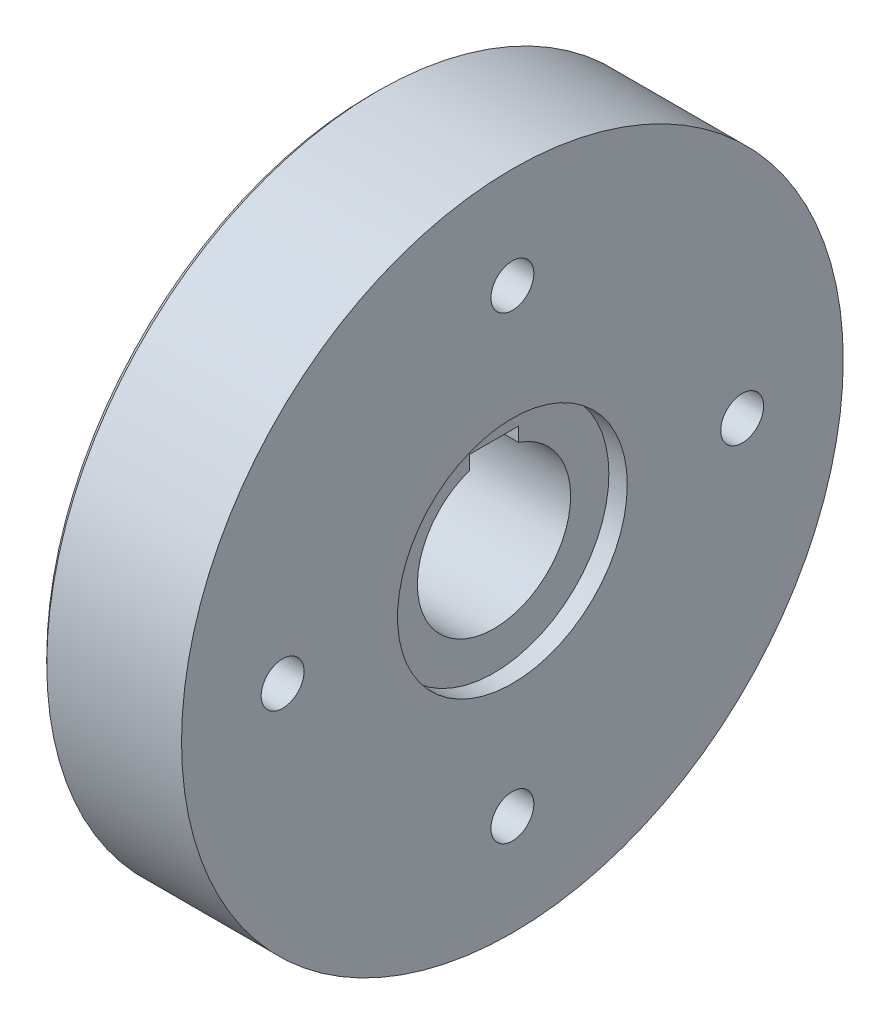
SolidWorks part; units mm, degrees
ref_plane "Front Plane" through (0, 0, 0) normal (0, 0, 1) x (1, 0, 0)
ref_plane "Top Plane" through (0, 0, 0) normal (0, 1, 0) x (1, 0, 0)
ref_plane "Right Plane" through (0, 0, 0) normal (1, 0, 0) x (0, 0, -1)
sketch "Sketch1" plane through (0, 0, 0) normal (0, 0, 1) x (1, 0, 0)
  line L0 (0, 0) -> (0, 15070.8085) construction
  line L1 (0, 0) -> (15070.8085, 0) construction
  line L2 (-40, 0) -> (40, 0)
  line L3 (-40, 25) -> (40, 25)
  line L4 (40, 108) -> (15, 108)
  line L5 (-40, 50) -> (15, 50)
  line L6 (15, 108) -> (15, 50)
  line L7 (-40, 50) -> (-40, 25)
  line L8 (40, 108) -> (40, 37.5)
  line L9 (40, 37.5) -> (45, 37.5)
  line L10 (45, 37.5) -> (45, 25)
  line L11 (45, 25) -> (40, 25)
  point P7 (0, 0)
  point P10 (0, 25)
  dimension "D1" = 80
  dimension "D2" = 50
  dimension "D3" = 216
  dimension "D4" = 25
  dimension "D5" = 100
  dimension "D6" = 75
  dimension "D7" = 5
revolve "Revolve1" add sketch "Sketch1" angle 360 about L2
sketch "Sketch2" plane through (40, 0, 0) normal (1, 0, 0) x (0, 0, -1)
  circle A0 centre (0, 0) radius 75 construction
  point P4 (0, 75)
  point P11 (75, 0)
  point P12 (0, -75)
  point P13 (-75, 0)
  dimension "D1" = 150
  dimension "D2" = 4
hole_wizard "M16x2.0 Tapped Hole1" positions "Sketch2" profile "Sketch3" tap size "M16x2.0" standard "ANSI Metric" end condition through all
sketch "Sketch3" plane through (40, 0, 75) normal (0, 1, 0) x (0, 0, -1)
  line L0 (0, 0) -> (0, 80)
  line L1 (0, 80) -> (7, 80)
  line L2 (7, 80) -> (7, 0)
  line L5 (7, 0) -> (0, 0)
  line L11 (0, -6.35) -> (0, 107.95) construction
  dimension "Thru Tap Drill Dia." = 14
  dimension "Thru Tap Drill Depth" = 80
cosmetic thread "Hole Thread1" parameters "D2"=16
cosmetic thread "Hole Thread2" parameters "D2"=16
cosmetic thread "Hole Thread3" parameters "D2"=16
cosmetic thread "Hole Thread4" parameters "D2"=16
sketch "Sketch4" plane through (0, 0, 0) normal (0, 0, 1) x (1, 0, 0)
  line L0 (15, 108) -> (-6, 108)
  line L1 (-6, 108) -> (-6, 100)
  line L2 (-6, 100) -> (15, 100)
  line L3 (15, 108) -> (15, -108) construction
  line L4 (15, 100) -> (15, 108)
  line L5 (0, 0) -> (133.487, 0) construction
  line L6 (40, -108) -> (40, 108) construction
  dimension "D1" = 200
  dimension "D2" = 46
revolve "Revolve2" add sketch "Sketch4" angle 360 about L5
sketch "Sketch5" plane through (0, 0, 0) normal (0, 0, 1) x (1, 0, 0)
  line L0 (-40, 0) -> (45, 0) construction
  line L1 (-40, 50) -> (-40, -50) construction
  line L2 (45, -37.5) -> (45, 37.5) construction
  line L4 (-40, 0) -> (45, 0)
  line L5 (-40, 0) -> (-40, 27.55)
  line L6 (-40, 27.55) -> (45, 28.4)
  line L7 (45, 0) -> (45, 28.4)
  line L8 (-40, -25) -> (45, -25) construction
  dimension "D1" = 53.4
  dimension "D2" = 52.55
extrude "Cut-Extrude1" cut sketch "Sketch5" against normal mid plane 16
chamfer "Chamfer2" distance 2 angle 45 4 edges at (45, 0, 37.5) (15, 0, 50) (-40, 0, 50) (-6, 0, 108)
sketch "Sketch6" plane through (45, 0, 0) normal (1, 0, 0) x (0, 0, -1)
  circle A0 centre (0, 0) radius 37.5
  circle A1 centre (0, 0) radius 37.5 construction
extrude "Cut-Extrude2" cut sketch "Sketch6" against normal blind 11
